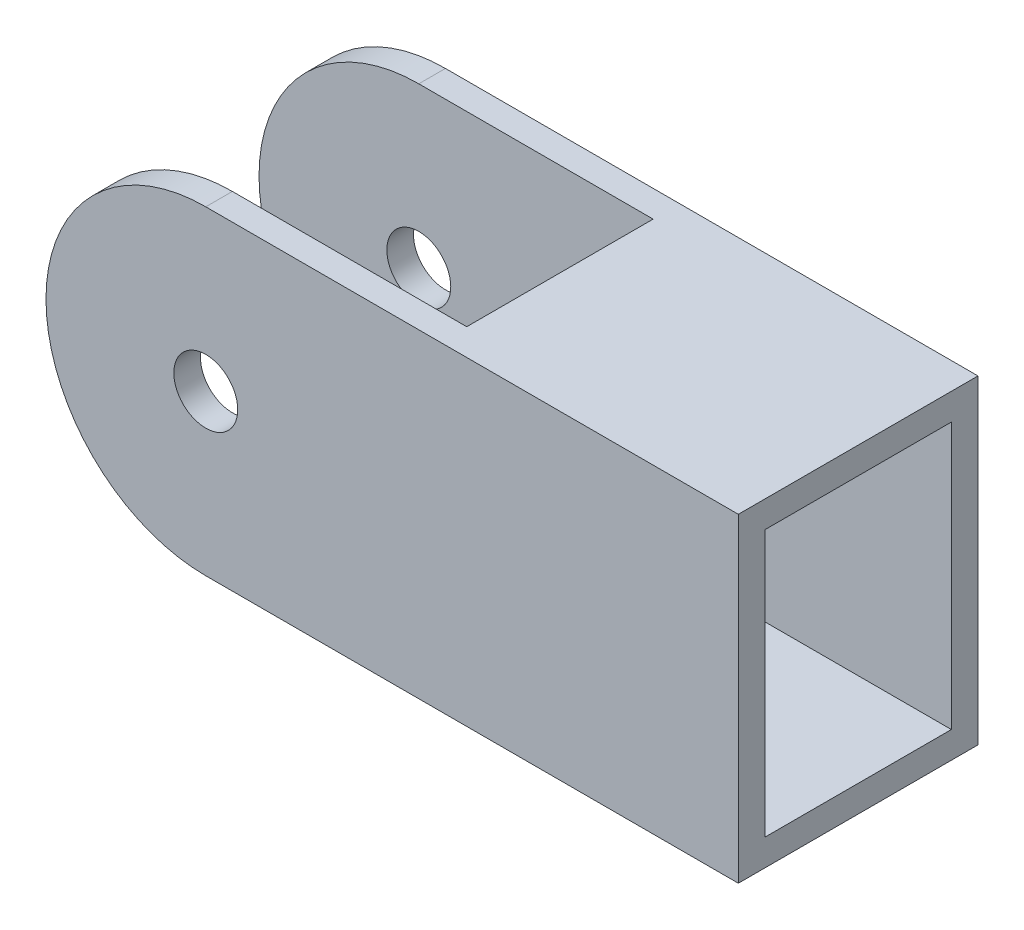
SolidWorks part; units mm, degrees
ref_plane "Płaszczyzna przednia" through (0, 0, 0) normal (0, 0, 1) x (1, 0, 0)
ref_plane "Płaszczyzna górna" through (0, 0, 0) normal (0, 1, 0) x (1, 0, 0)
ref_plane "Płaszczyzna prawa" through (0, 0, 0) normal (1, 0, 0) x (0, 0, -1)
sketch "Szkic1" plane through (0, 0, 0) normal (0, 0, 1) x (1, 0, 0)
  line L1 (-50, -30) -> (50, -30)
  line L3 (-50, 30) -> (50, 30)
  line L4 (50, -30) -> (50, 30)
  line L5 (-50, -30) -> (50, 30) construction
  line L6 (-50, 30) -> (50, -30) construction
  arc A0 (-50, -30) -> (-50, 30) centre (-50, 0) cw
  point P0 (0, 0)
  dimension "D1" = 60
  dimension "D2" = 100
extrude "Dodanie-wyciągnięcie1" add sketch "Szkic1" along normal blind 5
ref_plane "Płaszczyzna1" through (0, 0, 22.5) normal (0, 0, 1) x (1, 0, 0)
mirror "Lustro2" about plane through (0, 0, 22.5) normal (0, 0, 1) of bodies 101
sketch "Szkic2" plane through (0, 30, 0) normal (0, 1, 0) x (1, 0, 0)
  line L0 (50, -5) -> (-50, -5) construction
  line L1 (50, -40) -> (-6, -40)
  line L2 (50, -40) -> (50, -5)
  line L3 (50, -5) -> (-6, -5)
  line L4 (-6, -40) -> (-6, -5)
  dimension "D1" = 56
extrude "Dodanie-wyciągnięcie2" add sketch "Szkic2" against normal blind 5 contours L3 L4 L1 L2
mirror "Lustro3" about plane through (0, 0, 0) normal (0, 1, 0) of "Dodanie-wyciągnięcie2"
sketch "Szkic3" plane through (0, 0, 45) normal (0, 0, 1) x (1, 0, 0)
  circle A0 centre (-50, 0) radius 6
  arc A1 (-50, 30) -> (-50, -30) centre (-50, 0) ccw construction
  dimension "D1" = 12
extrude "Wytnij-wyciągnięcie1" cut sketch "Szkic3" against normal through all contours A0
